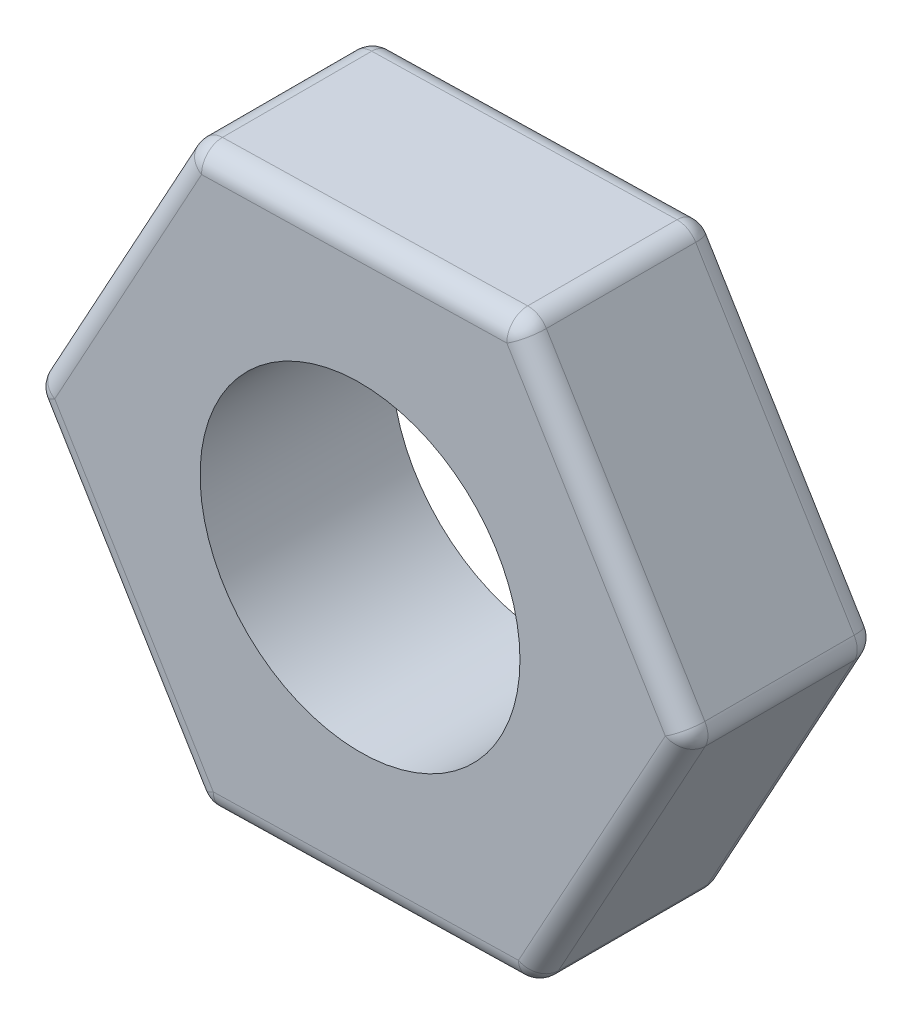
SolidWorks part; units mm, degrees
ref_plane "前视基准面" through (0, 0, 0) normal (0, 0, 1) x (1, 0, 0)
ref_plane "上视基准面" through (0, 0, 0) normal (0, 1, 0) x (1, 0, 0)
ref_plane "右视基准面" through (0, 0, 0) normal (1, 0, 0) x (0, 0, -1)
sketch "草图1" plane through (0, 0, 0) normal (0, 0, 1) x (1, 0, 0)
  line L1 (-1.488, -2.7134) -> (1.6059, -2.6453)
  line L2 (1.6059, -2.6453) -> (3.0938, 0.0681)
  line L3 (3.0938, 0.0681) -> (1.488, 2.7134)
  line L4 (1.488, 2.7134) -> (-1.6059, 2.6453)
  line L5 (-1.6059, 2.6453) -> (-3.0938, -0.0681)
  line L6 (-3.0938, -0.0681) -> (-1.488, -2.7134)
  circle A0 centre (0, 0) radius 2.68 construction
  circle A1 centre (0, 0) radius 1.5
  dimension "D1" = 5.36
extrude "凸台-拉伸1" add sketch "草图1" along normal blind 1.8
fillet "圆角2" radius 0.2 18 edges at (-0.0589, 2.6794, 0) (2.2909, 1.3907, 0) (2.3499, -1.2886, 0) (0.0589, -2.6794, 0) (-2.2909, -1.3907, 0) (-2.3499, 1.2886, 0) (-2.2909, -1.3907, 1.8) (0.0589, -2.6794, 1.8) (2.3499, -1.2886, 1.8) (2.2909, 1.3907, 1.8) (-0.0589, 2.6794, 1.8) (-2.3499, 1.2886, 1.8) (-1.488, -2.7134, 0.9) (-3.0938, -0.0681, 0.9) (1.6059, -2.6453, 0.9) (3.0938, 0.0681, 0.9) (1.488, 2.7134, 0.9) (-1.6059, 2.6453, 0.9)
